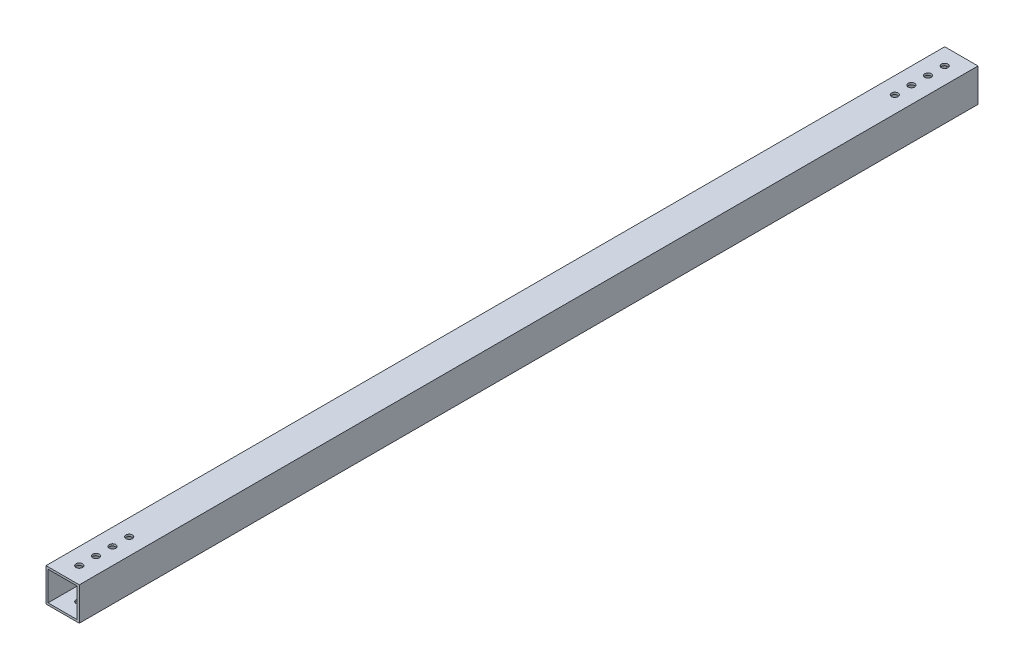
SolidWorks part; units mm, degrees
material "6061-T6 (SS)"
ref_plane "Front Plane" through (0, 0, 0) normal (0, 0, 1) x (1, 0, 0)
ref_plane "Top Plane" through (0, 0, 0) normal (0, 1, 0) x (1, 0, 0)
ref_plane "Right Plane" through (0, 0, 0) normal (1, 0, 0) x (0, 0, -1)
sketch "Sketch1" plane through (0, 0, 0) normal (0, 0, 1) x (1, 0, 0)
  line L1 (-12.7, -12.7) -> (12.7, -12.7)
  line L2 (-12.7, -12.7) -> (-12.7, 12.7)
  line L3 (-12.7, 12.7) -> (12.7, 12.7)
  line L4 (12.7, -12.7) -> (12.7, 12.7)
  line L5 (-12.7, -12.7) -> (12.7, 12.7) construction
  line L6 (-12.7, 12.7) -> (12.7, -12.7) construction
  point P0 (0, 0)
  dimension "D1" = 25.4
extrude "Boss-Extrude1" add sketch "Sketch1" along normal mid plane 685.8
shell "Shell1" thickness 1.5875
sketch "Sketch2" plane through (0, 0, 0) normal (0, 1, 0) x (1, 0, 0)
  line L0 (12.7, -342.9) -> (-12.7, -342.9) construction
  circle A0 centre (0, -330.2) radius 2.4892
  circle A1 centre (0, -317.5) radius 2.4892
  circle A2 centre (0, -304.8) radius 2.4892
  circle A3 centre (0, -292.1) radius 2.4892
  dimension "D1" = 4.9784
  dimension "D4" = 12.7
  dimension "D2" = 12.7
  dimension "D3" = 4
extrude "Cut-Extrude1" cut sketch "Sketch2" against normal through all both and the other way through all
mirror "Mirror1" about plane through (0, 0, 0) normal (0, 0, 1) of "Cut-Extrude1"
